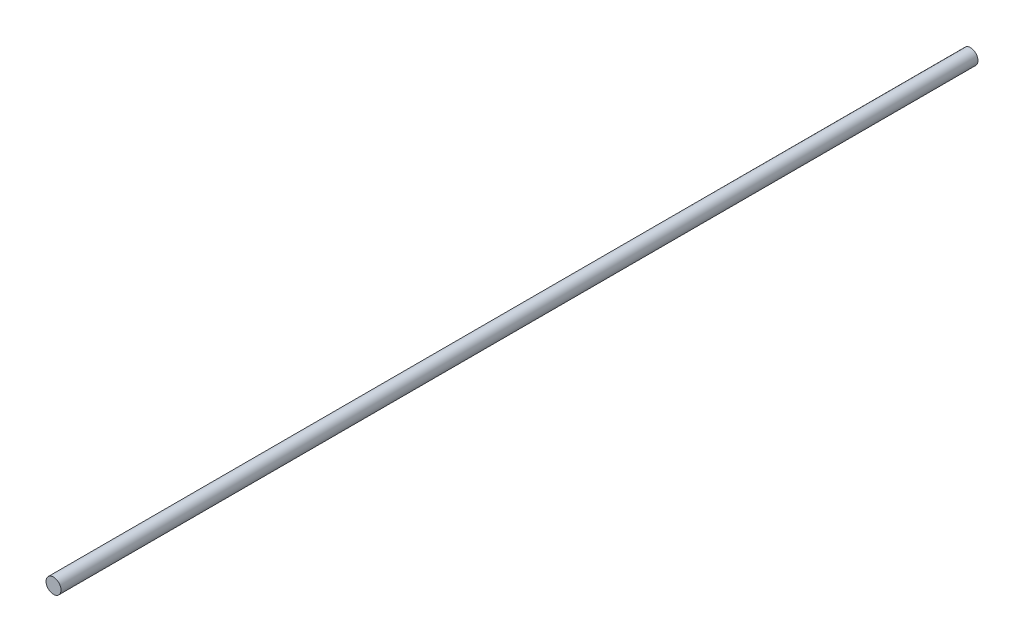
SolidWorks part; units mm, degrees
ref_plane "Front Plane" through (0, 0, 0) normal (0, 0, 1) x (1, 0, 0)
ref_plane "Top Plane" through (0, 0, 0) normal (0, 1, 0) x (1, 0, 0)
ref_plane "Right Plane" through (0, 0, 0) normal (1, 0, 0) x (0, 0, -1)
sketch "Sketch1" plane through (0, 0, 0) normal (0, 0, 1) x (1, 0, 0)
  circle A0 centre (0, 0) radius 4
  dimension "D1" = 8
extrude "Boss-Extrude1" add sketch "Sketch1" along normal blind 489
